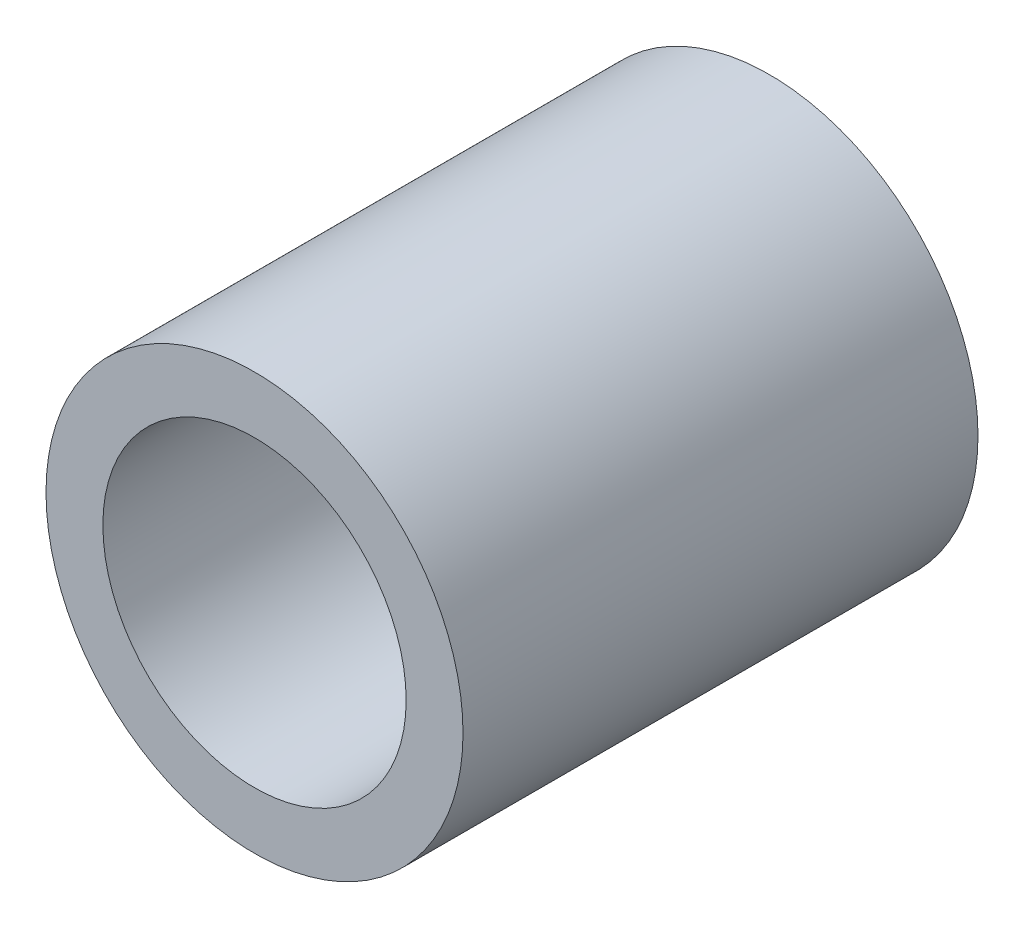
SolidWorks part; units mm, degrees
material "PVC Rigid"
ref_plane "Front Plane" through (0, 0, 0) normal (0, 0, 1) x (1, 0, 0)
ref_plane "Top Plane" through (0, 0, 0) normal (0, 1, 0) x (1, 0, 0)
ref_plane "Right Plane" through (0, 0, 0) normal (1, 0, 0) x (0, 0, -1)
sketch "Sketch1" plane through (0, 0, 0) normal (0, 0, 1) x (1, 0, 0)
  circle A0 centre (0, 0) radius 6.35
  circle A1 centre (0, 0) radius 8.7312
  dimension "D1" = 12.7
  dimension "D2" = 17.4625
extrude "Boss-Extrude1" add sketch "Sketch1" along normal up to surface (21.5645 mm away)
